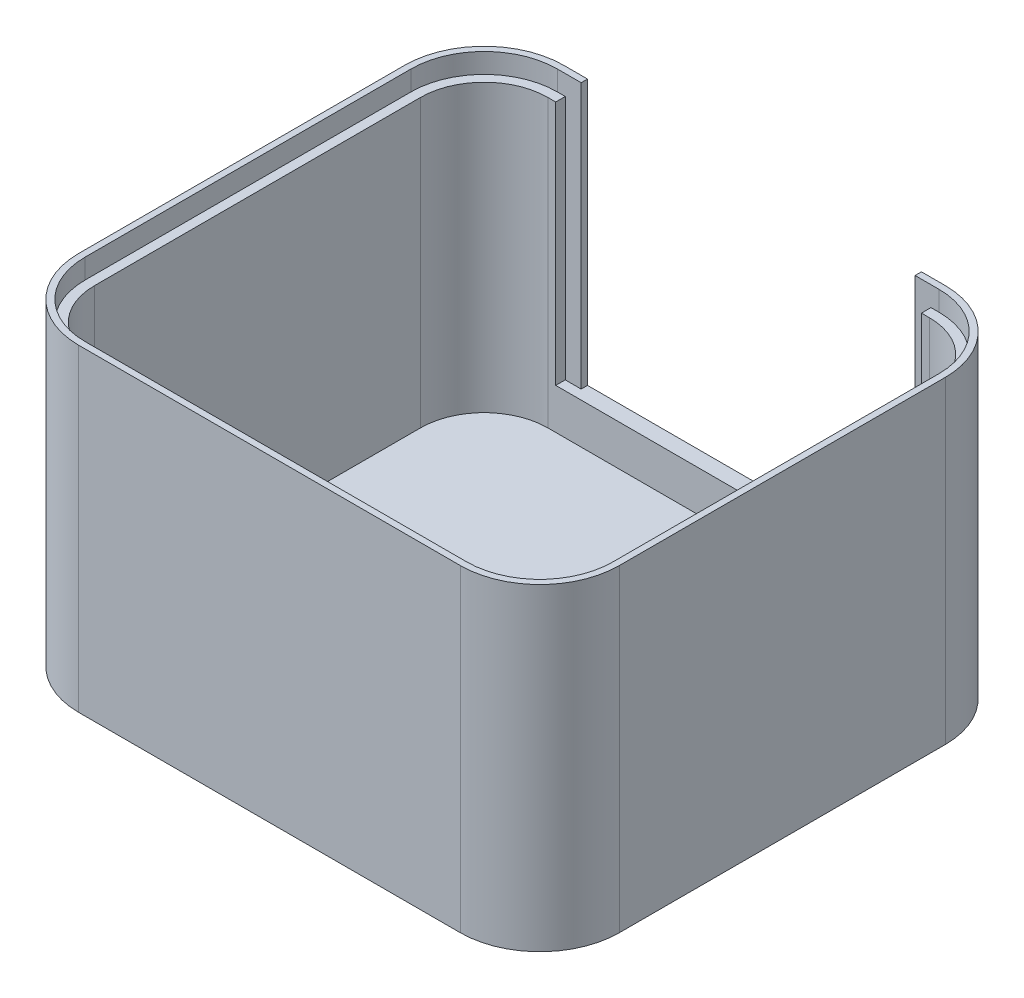
SolidWorks part; units mm, degrees
material "ABS"
ref_plane "Front Plane" through (0, 0, 0) normal (0, 0, 1) x (1, 0, 0)
ref_plane "Top Plane" through (0, 0, 0) normal (0, 1, 0) x (1, 0, 0)
ref_plane "Right Plane" through (0, 0, 0) normal (1, 0, 0) x (0, 0, -1)
sketch "Sketch1" plane through (0, 0, 0) normal (0, 1, 0) x (1, 0, 0)
  line L1 (-68, 61) -> (68, 61)
  line L2 (-68, 61) -> (-68, -61)
  line L3 (-68, -61) -> (68, -61)
  line L4 (68, 61) -> (68, -61)
  line L5 (-68, 61) -> (68, -61) construction
  line L6 (-68, -61) -> (68, 61) construction
  point P0 (0, 0)
  dimension "D1" = 136
  dimension "D2" = 122
extrude "Boss-Extrude1" add sketch "Sketch1" along normal blind 80
fillet "Fillet1" radius 20 4 edges at (-68, 40, 61) (68, 40, 61) (68, 40, -61) (-68, 40, -61)
shell "Shell1" thickness 4
sketch "Sketch5" plane through (0, 80, 0) normal (0, 1, 0) x (1, 0, 0)
  line L12 (48, 57) -> (-48, 57) construction
  line L13 (64, -41) -> (64, 41) construction
  line L14 (-48, -57) -> (48, -57) construction
  line L15 (-64, 41) -> (-64, -41) construction
  line L16 (48, 57) -> (-48, 57)
  line L17 (64, -41) -> (64, 41)
  line L18 (-48, -57) -> (48, -57)
  line L19 (-64, 41) -> (-64, -41)
  line L20 (48, 59.4) -> (-48, 59.4)
  line L21 (-66.4, 41) -> (-66.4, -41)
  line L22 (-48, -59.4) -> (48, -59.4)
  line L23 (66.4, -41) -> (66.4, 41)
  arc A12 (64, 41) -> (48, 57) centre (48, 41) ccw construction
  arc A13 (48, -57) -> (64, -41) centre (48, -41) ccw construction
  arc A14 (-64, -41) -> (-48, -57) centre (-48, -41) ccw construction
  arc A15 (-48, 57) -> (-64, 41) centre (-48, 41) ccw construction
  arc A16 (64, 41) -> (48, 57) centre (48, 41) ccw
  arc A17 (48, -57) -> (64, -41) centre (48, -41) ccw
  arc A18 (-64, -41) -> (-48, -57) centre (-48, -41) ccw
  arc A19 (-48, 57) -> (-64, 41) centre (-48, 41) ccw
  arc A20 (-48, 59.4) -> (-66.4, 41) centre (-48, 41) ccw
  arc A21 (-66.4, -41) -> (-48, -59.4) centre (-48, -41) ccw
  arc A22 (48, -59.4) -> (66.4, -41) centre (48, -41) ccw
  arc A23 (66.4, 41) -> (48, 59.4) centre (48, 41) ccw
  dimension "D1" = 2.4
extrude "Cut-Extrude2" cut sketch "Sketch5" against normal blind 5
hole_wizard "#4 Clearance Hole1" positions "Sketch6" profile "Sketch7" hole size "#4" standard "ANSI Inch" end condition through all
sketch "Sketch6" plane through (0, 3, 0) normal (0, 1, 0) x (1, 0, 0)
  line L0 (-44, 0) -> (44, 0) construction
  line L2 (0, 40.9794) -> (0, -38.413) construction
  line L3 (0, -44) -> (0, 44) construction
  point P0 (-25.4, 0)
  point P15 (25.4, 0)
  dimension "D1" = 50.8
sketch "Sketch7" plane through (-25.4, 3, 0) normal (1, 0, 0) x (0, 0, 1)
  line L0 (0, 0) -> (0, 3)
  line L1 (0, 3) -> (1.6319, 3)
  line L2 (1.6319, 3) -> (1.6319, 0)
  line L5 (1.6319, 0) -> (0, 0)
  line L11 (0, -6.35) -> (0, 107.95) construction
  dimension "Thru Hole Dia." = 3.2639
  dimension "Thru Hole Depth" = 3
sketch "Sketch8" plane through (0, 80, 0) normal (0, 1, 0) x (1, 0, 0)
  line L0 (0, 61) -> (0, 57) construction
  line L1 (48, 61) -> (-48, 61) construction
  line L2 (0, -44) -> (0, 44) construction
  line L15 (48, 57) -> (-48, 57) construction
  line L16 (42, 61) -> (-42, 61)
  line L17 (-42, 61) -> (-42, 59.4)
  line L18 (48, 59.4) -> (-48, 59.4) construction
  line L19 (-42, 59.4) -> (-46, 59.4)
  line L20 (-46, 59.4) -> (-46, 57)
  line L21 (-46, 57) -> (46, 57)
  line L22 (46, 59.4) -> (46, 57)
  line L23 (42, 59.4) -> (46, 59.4)
  line L24 (42, 61) -> (42, 59.4)
  dimension "D1" = 4
  dimension "D2" = 84
extrude "Cut-Extrude3" cut sketch "Sketch8" against normal blind 66.75
